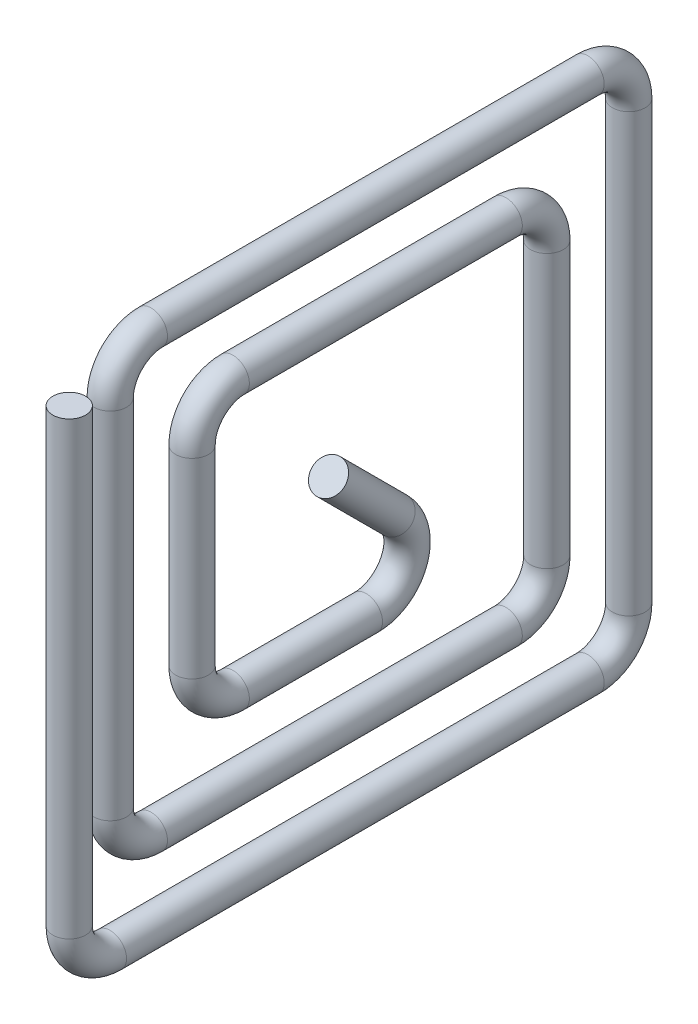
SolidWorks part; units mm, degrees
ref_plane "Спереди" through (0, 0, 0) normal (0, 0, 1) x (1, 0, 0)
ref_plane "Сверху" through (0, 0, 0) normal (0, 1, 0) x (1, 0, 0)
ref_plane "Справа" through (0, 0, 0) normal (1, 0, 0) x (0, 0, -1)
sketch "Эскиз1" plane through (0, 0, 0) normal (1, 0, 0) x (0, 0, -1)
  line L1 (-5, -5) -> (5, -5) construction
  line L2 (-5, -5) -> (-5, 5) construction
  line L3 (-5, 5) -> (5, 5) construction
  line L4 (5, -5) -> (5, 5) construction
  line L5 (-5, -5) -> (5, 5) construction
  line L6 (-5, 5) -> (5, -5) construction
  line L7 (-5, 5) -> (8, 5) construction
  line L8 (-5, 5) -> (-5, -8) construction
  line L9 (-5, -8) -> (8, -8) construction
  line L10 (8, 5) -> (8, -8) construction
  line L11 (8, -8) -> (-8, -8) construction
  line L12 (8, -8) -> (8, 8) construction
  line L13 (8, 8) -> (-8, 8) construction
  line L14 (-8, -8) -> (-8, 8) construction
  line L15 (-8, 8) -> (11, 8) construction
  line L16 (-8, 8) -> (-8, -11) construction
  line L17 (-8, -11) -> (11, -11) construction
  line L18 (11, 8) -> (11, -11) construction
  line L19 (11, -11) -> (-11, -11) construction
  line L20 (11, -11) -> (11, 11) construction
  line L21 (11, 11) -> (-11, 11) construction
  line L22 (-11, -11) -> (-11, 11) construction
  point P0 (0, 0)
  dimension "D1" = 10
  dimension "D2" = 13
  dimension "D3" = 16
  dimension "D4" = 19
  dimension "D5" = 22
sketch "Эскиз2" plane through (0, 0, 0) normal (1, 0, 0) x (0, 0, -1)
  line L0 (0, 0) -> (2.4393, -2.4393)
  line L1 (-5, 5) -> (5, -5) construction
  line L2 (1.3787, -5) -> (-3.5, -5)
  line L3 (-5, -3.5) -> (-5, 3.5)
  line L4 (-3.5, 5) -> (6.5, 5)
  line L5 (8, 3.5) -> (8, -6.5)
  line L6 (6.5, -8) -> (-6.5, -8)
  line L7 (-8, -6.5) -> (-8, 6.5)
  line L8 (-6.5, 8) -> (9.5, 8)
  line L9 (11, 6.5) -> (11, -9.5)
  line L10 (9.5, -11) -> (-8, -11)
  line L11 (11, -11) -> (-11, -11) construction
  line L12 (-9.5, -9.5) -> (-9.5, 7)
  arc A0 (-3.5, 5) -> (-5, 3.5) centre (-3.5, 3.5) ccw
  arc A1 (-5, -3.5) -> (-3.5, -5) centre (-3.5, -3.5) ccw
  arc A2 (-9.5, -9.5) -> (-8, -11) centre (-8, -9.5) ccw
  arc A3 (9.5, -11) -> (11, -9.5) centre (9.5, -9.5) ccw
  arc A4 (9.5, 8) -> (11, 6.5) centre (9.5, 6.5) cw
  arc A5 (-6.5, 8) -> (-8, 6.5) centre (-6.5, 6.5) ccw
  arc A6 (-8, -6.5) -> (-6.5, -8) centre (-6.5, -6.5) ccw
  arc A7 (6.5, -8) -> (8, -6.5) centre (6.5, -6.5) ccw
  arc A8 (8, 3.5) -> (6.5, 5) centre (6.5, 3.5) ccw
  arc A9 (1.3787, -5) -> (2.4393, -2.4393) centre (1.3787, -3.5) ccw
  point P27 (-5, 5)
  point P30 (-5, -5)
  point P33 (-9.5, -11)
  point P36 (11, -11)
  point P39 (11, 8)
  point P42 (-8, 8)
  point P45 (-8, -8)
  point P48 (8, -8)
  point P51 (8, 5)
  point P54 (5, -5)
  dimension "D3" = 1.5
  dimension "D4" = 1.5
  dimension "D1" = 1.5
  dimension "D2" = 18
ref_plane "Плоскость1" through (0, 7, 9.5) normal (0, 1, 0) x (1, 0, 0)
sketch "Эскиз3" plane through (0, 7, 9.5) normal (0, 1, 0) x (1, 0, 0)
  circle A0 centre (0, 0) radius 0.6
  dimension "D1" = 1.2
sweep "По траектории1" add profiles "Эскиз3" path "Эскиз2"
